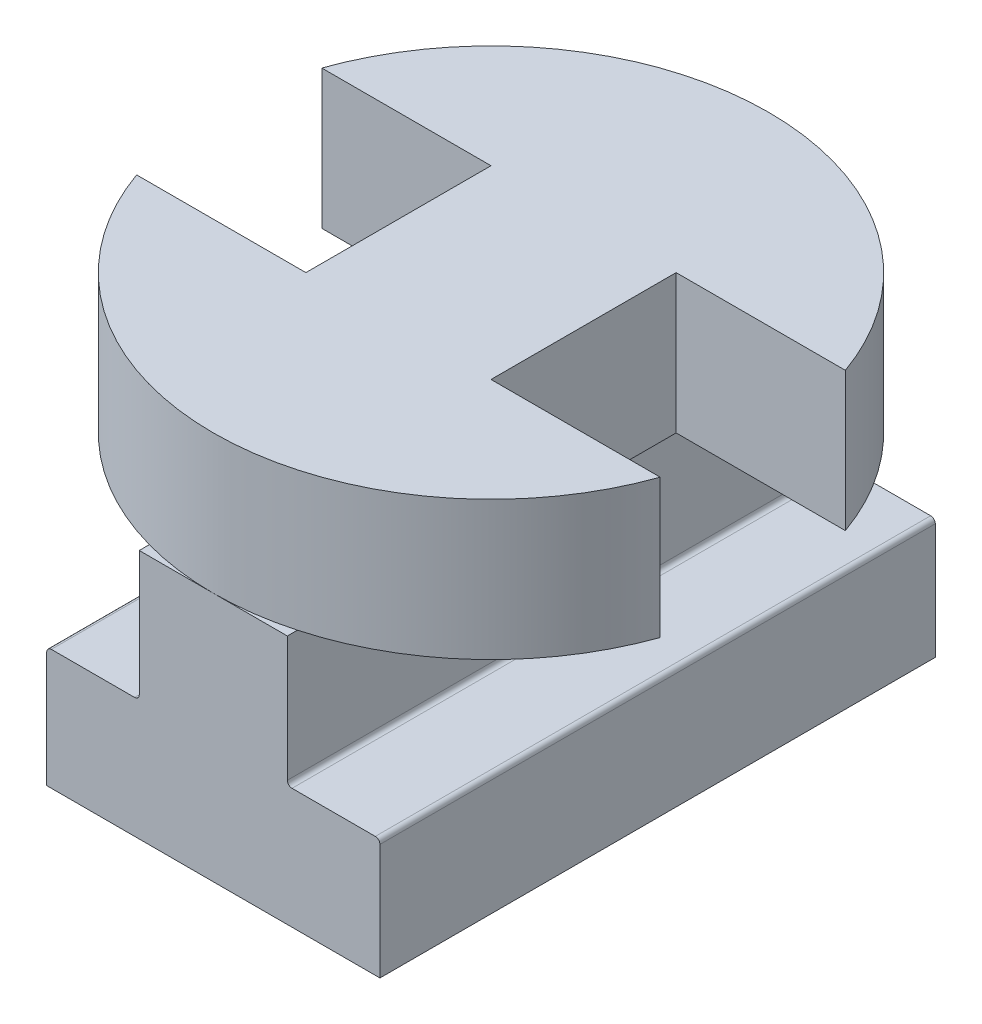
SolidWorks part; units mm, degrees
ref_plane "Front Plane" through (0, 0, 0) normal (0, 0, 1) x (1, 0, 0)
ref_plane "Top Plane" through (0, 0, 0) normal (0, 1, 0) x (1, 0, 0)
ref_plane "Right Plane" through (0, 0, 0) normal (1, 0, 0) x (0, 0, -1)
sketch "Sketch2" plane through (0, 0, 0) normal (0, 0, 1) x (1, 0, 0)
  line L0 (0, 0) -> (0, 2.7) construction
  line L1 (-2, 0) -> (-3, 0) construction
  line L2 (-3, 0) -> (-3, 2.7) construction
  line L3 (-3, 2.7) -> (-1, 2.7) construction
  line L4 (-1, 2.7) -> (-1, 1.5) construction
  line L5 (-1, 1.5) -> (-2, 1.5) construction
  line L6 (-2, 1.5) -> (-2, 0) construction
  line L7 (-2, 0) -> (0, 0) construction
  line L8 (0, 0) -> (0, 2.7) construction
  line L9 (0, 2.7) -> (-1, 2.7) construction
  line L10 (2, 1.5) -> (2, 0) construction
  line L11 (1, 1.5) -> (2, 1.5) construction
  line L12 (1, 2.7) -> (1, 1.5) construction
  line L13 (3, 2.7) -> (1, 2.7) construction
  line L14 (3, 0) -> (3, 2.7) construction
  line L15 (2, 0) -> (3, 0) construction
  line L16 (-1, 2.7) -> (-1, 1.5)
  line L17 (-1, 1.5) -> (-2, 1.5)
  line L18 (-2, 1.5) -> (-2, 0)
  line L19 (-0.8, 2.7) -> (-0.8, 1.3)
  line L20 (-0.8, 1.3) -> (-1.8, 1.3)
  line L21 (-1.8, 1.3) -> (-1.8, 0)
  line L22 (1.8, 1.3) -> (1.8, 0)
  line L23 (0.8, 1.3) -> (1.8, 1.3)
  line L24 (0.8, 2.7) -> (0.8, 1.3)
  line L25 (-1.8, 0) -> (1.8, 0)
  line L26 (-0.8, 2.7) -> (0.8, 2.7)
  dimension "D1" = 1
  dimension "D2" = 1.5
  dimension "D3" = 1.2
  dimension "D4" = 1
  dimension "D5" = 3
  dimension "D6" = 0.2
extrude "Boss-Extrude1" add sketch "Sketch2" along normal blind 6 contours L26 L19 L20 L21 L25 L22 L23 L24
sketch "Sketch3" plane through (0, 2.7, 0) normal (0, 1, 0) x (1, 0, 0)
  line L0 (0, -3) -> (0.8, -3) construction
  line L1 (0.8, -6) -> (0.8, 0) construction
  line L2 (0, -3) -> (0, 0) construction
  line L3 (-0.8, 0) -> (0.8, 0) construction
  line L4 (0, -3) -> (-3, -3) construction
  line L5 (-1, -2) -> (1, -2) construction
  line L6 (-1, -2) -> (-1, -4)
  line L7 (-1, -4) -> (1, -4) construction
  line L8 (1, -2) -> (1, -4)
  line L9 (-1, -2) -> (1, -4) construction
  line L10 (-1, -4) -> (1, -2) construction
  line L11 (-1, -2) -> (-2.8284, -2)
  line L12 (1, -2) -> (2.8284, -2)
  line L13 (1, -4) -> (2.8284, -4)
  line L14 (-1, -4) -> (-2.8284, -4)
  circle A0 centre (0, -3) radius 3
  circle A1 centre (-1.6, -3) radius 0.25 construction
  circle A2 centre (1.6, -3) radius 0.25 construction
  line M10 (-0.8, 0) -> (-0.8, -6)
  line M12 (0.8, -6) -> (0.8, 0)
  dimension "D1" = 6
  dimension "D3" = 0.5
  dimension "D2" = 2
  dimension "D4" = 3.2
  dimension "D5" = 1
extrude "Boss-Extrude2" add sketch "Sketch3" along normal blind 1.5 contours A0 M12 M10 | A0 L11 L6 L14 M10 | A0 L13 L8 L12 M12
sketch "Sketch9" [suppressed] plane through (0, 0, 0) normal (0, 0, -1) x (-1, 0, 0)
  line L0 (-0.8, 2.7) -> (-0.8, 1.3) construction
  line L1 (0.8, 2.7) -> (-0.8, 2.7) construction
  line L2 (0.8, 2.7) -> (0.8, 1.3) construction
  line L3 (0.8, 1.3) -> (1.8, 1.3) construction
  line L4 (1.8, 1.3) -> (1.8, 0) construction
  line L5 (1.8, 0) -> (-1.8, 0) construction
  line L6 (-1.8, 1.3) -> (-1.8, 0) construction
  line L7 (-0.8, 1.3) -> (-1.8, 1.3) construction
  line L8 (-0.8, 2.7) -> (-0.8, 1.3)
  line L9 (0.8, 2.7) -> (-0.8, 2.7)
  line L10 (0.8, 2.7) -> (0.8, 1.3)
  line L11 (0.8, 1.3) -> (1.8, 1.3)
  line L12 (1.8, 1.3) -> (1.8, 0)
  line L13 (1.8, 0) -> (-1.8, 0)
  line L14 (-1.8, 1.3) -> (-1.8, 0)
  line L15 (-0.8, 1.3) -> (-1.8, 1.3)
fillet "Fillet6" radius 0.05 4 edges at (-1.8, 1.3, 3) (1.8, 1.3, 3) (0.8, 1.3, 3) (-0.8, 1.3, 3)
sketch "Sketch13" plane through (0, 0, 0) normal (0, -1, 0) x (1, 0, 0)
  line L0 (0, 0) -> (0, 6)
equation "\"supportThickness\"=1.5"
equation "\"pcbThickness\"= 1.6"
equation "\"sideWallThickness\"= 1.5"
equation "\"bottomWallThickness\"= 6.0"
equation "\"topWallThickness\"= 2.0"
equation "\"wallTolerance\"= 0.2"
equation "\"totalHeight\"= 220.50 + \"wallTolerance\""
equation "\"totalWidth\"= 12 * \"motorDiameter\" + 11 * \"motor2motorHorizontal\" + 2 * \"wallTolerance\""
equation "\"totalDepth\"= 4 * \"motorDiameter\" + 2 * \"pcbThickness\" + 1 * \"motor2motorHorizontal\" + 4 * 0.10 + 2 * \"wallTolerance\""
equation "\"pinHeight\"= 115"
equation "\"pinWidth\"= 4.85"
equation "\"electricalComponents\"=53.04"
equation "\"motorDiameter\"=6.0"
equation "\"res\"= 2.0"
equation "\"pcbWidth\"= 106.67"
equation "\"supportDistance\"= 10.0"
equation "\"pcbLength\"= 216.23"
equation "\"motorSmallDiameter\"= 3.5"
equation "\"motorSmallLength\"= 0.4"
equation "\"motorShaftDiameter\"= 2.0"
equation "\"motorShaftLength\"= 2.7"
equation "\"motorShaftFlatDist\"= 1.5"
equation "\"motorWireDiameter\"= 0.5"
equation "\"motorWireDistance\"= 3.20"
equation "\"encoderLength\"= 3.2"
equation "\"encoderWidth\"= 1.7"
equation "\"encoderDepth\"=1.1"
equation "\"encoderTolerance\"=0.15"
equation "\"encoderDistance\"=1.0"
equation "\"pcbToWall\"= \"motorDiameter\" + \"wallTolerance\""
equation "\"pcbToPcb\"= 2 * \"motorDiameter\" + \"wallTolerance\" + 1.0"
equation "\"bracketBlockLength\"= 18.0"
equation "\"bracketBlockWidth\"= 13.20"
equation "\"bracketBlockHeight\"= 10.0"
equation "\"bracketShortLength\"= \"totalDepth\""
equation "\"bracketShortWidth\"= 18.0"
equation "\"bracketShortWall\"= 2.0"
equation "\"bracketLongWall\"= 2.0"
equation "\"bracketLongLength\"= \"totalDepth\" - \"bracketLongWall\""
equation "\"bracketLongWidth\"= 15.0"
equation "\"D1@Boss-Extrude1\"=\"motorDiameter\""
equation "\"D1@Sketch3\"=\"motorDiameter\""
equation "\"D3@Sketch3\"=\"motorWireDiameter\""
equation "\"D4@Sketch3\"=\"motorWireDistance\""
